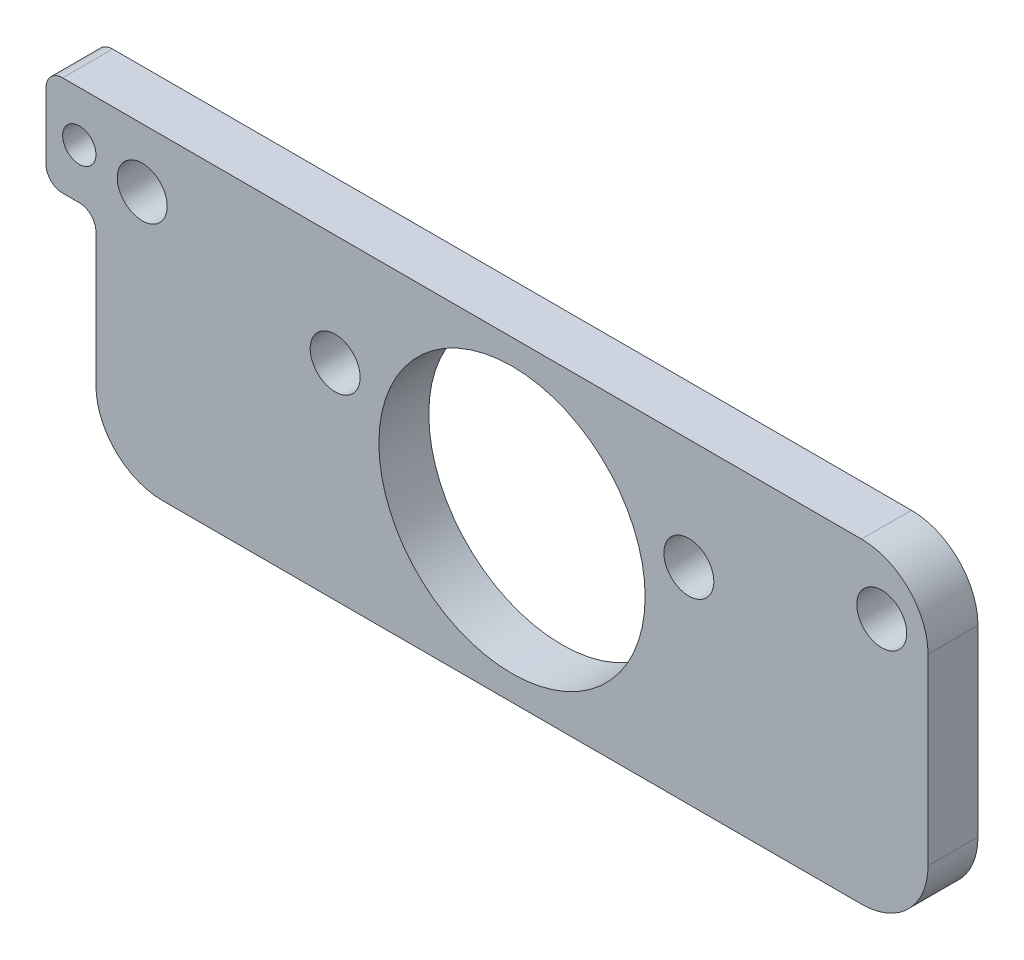
SolidWorks part; units mm, degrees
ref_plane "Front" through (0, 0, 0) normal (0, 0, 1) x (1, 0, 0)
ref_plane "Top" through (0, 0, 0) normal (0, 1, 0) x (1, 0, 0)
ref_plane "Right" through (0, 0, 0) normal (1, 0, 0) x (0, 0, -1)
sketch "Эскиз1" plane through (0, 0, 0) normal (0, 0, 1) x (1, 0, 0)
  line L0 (-1.0263, 8.6597) -> (-1.0263, -10.3403) construction
  line L1 (-22.0263, -10.3403) -> (19.9737, -10.3403)
  line L3 (-22.0263, 8.6597) -> (19.9737, 8.6597)
  line L5 (-26.0263, -6.3403) -> (-26.0263, 1.6597)
  line L6 (23.9737, 4.6597) -> (23.9737, -6.3403)
  line L7 (-1.0263, -0.8403) -> (-23.2426, 5.1125) construction
  line L8 (-22.0263, 8.6597) -> (-28.0263, 8.6597)
  line L9 (-29.0263, 7.6597) -> (-29.0263, 3.6597)
  line L10 (-28.0263, 2.6597) -> (-27.0263, 2.6597)
  circle A0 centre (-1.0263, -0.8403) radius 8
  arc A1 (19.9737, -10.3403) -> (23.9737, -6.3403) centre (19.9737, -6.3403) ccw
  arc A2 (-22.0263, -10.3403) -> (-26.0263, -6.3403) centre (-22.0263, -6.3403) cw
  arc A4 (19.9737, 8.6597) -> (23.9737, 4.6597) centre (19.9737, 4.6597) cw
  circle A5 centre (-23.2426, 5.1125) radius 1.5
  circle A6 centre (-11.6515, 2.0067) radius 1.5
  circle A7 centre (9.5988, 2.0067) radius 1.5
  circle A8 centre (21.19, 5.1125) radius 1.5
  arc A9 (-26.0263, 1.6597) -> (-27.0263, 2.6597) centre (-27.0263, 1.6597) ccw
  arc A10 (-28.0263, 8.6597) -> (-29.0263, 7.6597) centre (-28.0263, 7.6597) ccw
  arc A11 (-29.0263, 3.6597) -> (-28.0263, 2.6597) centre (-28.0263, 3.6597) ccw
  circle A12 centre (-27.0263, 5.6597) radius 1
  point P11 (23.9737, -10.3403)
  point P14 (-26.0263, -10.3403)
  point P17 (-26.0263, 8.6597)
  point P20 (23.9737, 8.6597)
  point P39 (0, 0)
  point P40 (0, 0)
  point P41 (-27.5263, 2.6597)
  dimension "D1" = 16
  dimension "D4" = 4
  dimension "D5" = 12
  dimension "D10" = 1
  dimension "D11" = 3
  dimension "D2" = 50
  dimension "D3" = 50
  dimension "D6" = 9.5
  dimension "D7" = 75
  dimension "D8" = 11
  dimension "D9" = 19
  dimension "D12" = 2
  dimension "D14" = 3
  dimension "D15" = 6
extrude "Бобышка-Вытянуть1" add sketch "Эскиз1" along normal blind 3
